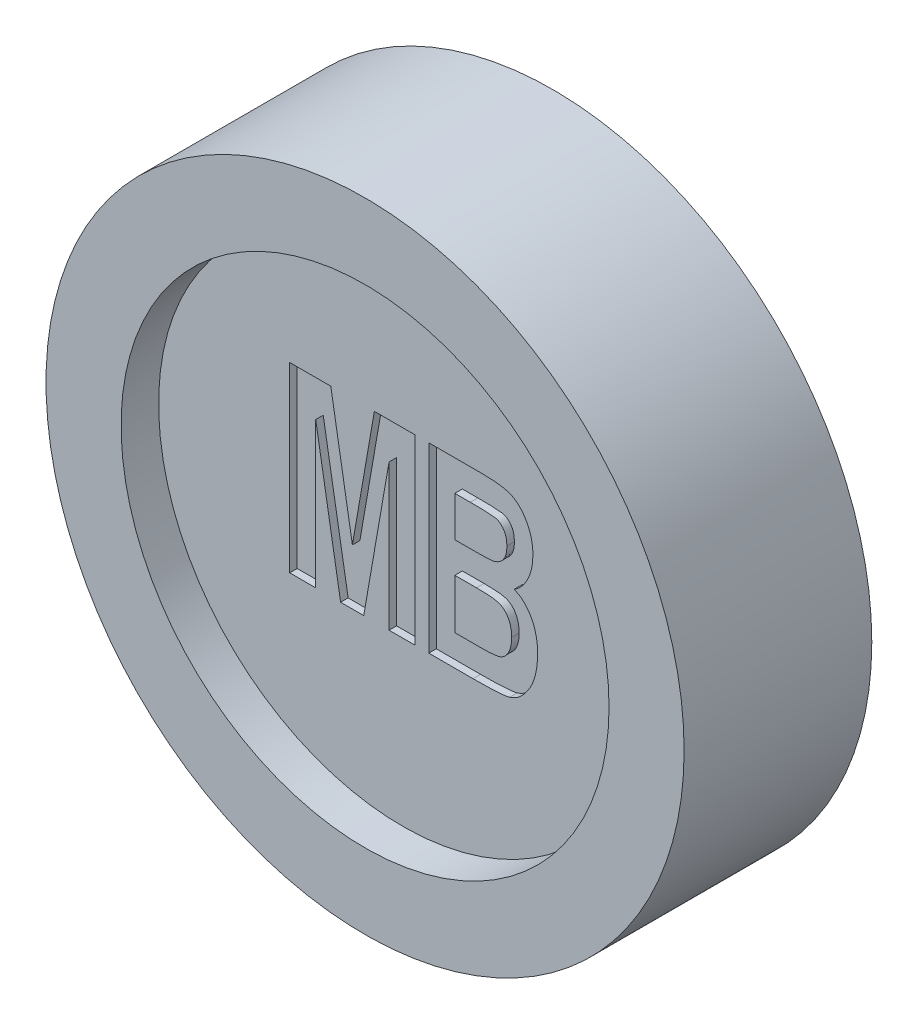
SolidWorks part; units mm, degrees
ref_plane "Front Plane" through (0, 0, 0) normal (0, 0, 1) x (1, 0, 0)
ref_plane "Top Plane" through (0, 0, 0) normal (0, 1, 0) x (1, 0, 0)
ref_plane "Right Plane" through (0, 0, 0) normal (1, 0, 0) x (0, 0, -1)
sketch "Sketch1" plane through (0, 0, 0) normal (0, 0, 1) x (1, 0, 0)
  circle A0 centre (0, 0) radius 10.795
  dimension "D1" = 21.59
extrude "Boss-Extrude1" add sketch "Sketch1" along normal blind 6.35
sketch "Sketch2" plane through (0, 0, 0) normal (0, 0, -1) x (-1, 0, 0)
  circle A1 centre (0, 0) radius 10.795
  circle A2 centre (0, 0) radius 10.795
  dimension "D1" = 0
sketch "Sketch3" plane through (0, 0, 6.35) normal (0, 0, 1) x (1, 0, 0)
  circle A0 centre (0, 0) radius 8.255
  dimension "D1" = 16.51
extrude "Cut-Extrude1" cut sketch "Sketch3" against normal blind 1.27 contours A0
sketch "Sketch4" plane through (0, 0, 0) normal (0, 0, -1) x (-1, 0, 0)
  circle A0 centre (0, 0) radius 8.255
  dimension "D1" = 16.51
extrude "Cut-Extrude2" cut sketch "Sketch4" against normal blind 1.27
sketch "Sketch6" plane through (0, 0, 5.08) normal (0, 0, 1) x (1, 0, 0)
  text T0 "MB\r\n" font "Arial Narrow" height in points 24
extrude "Cut-Extrude3" cut sketch "Sketch6" against normal blind 0.254
sketch "Sketch7" plane through (0, 0, 1.27) normal (0, 0, -1) x (-1, 0, 0)
  text T0 "Connect" font "Arial Narrow" height in points 11
extrude "Cut-Extrude4" cut sketch "Sketch7" against normal blind 0.254
sketch "Sketch8" plane through (0, 0, 1.27) normal (0, 0, -1) x (-1, 0, 0)
  text T0 "Four" font "Arial Narrow" height in points 11
extrude "Cut-Extrude5" cut sketch "Sketch8" against normal blind 0.254
